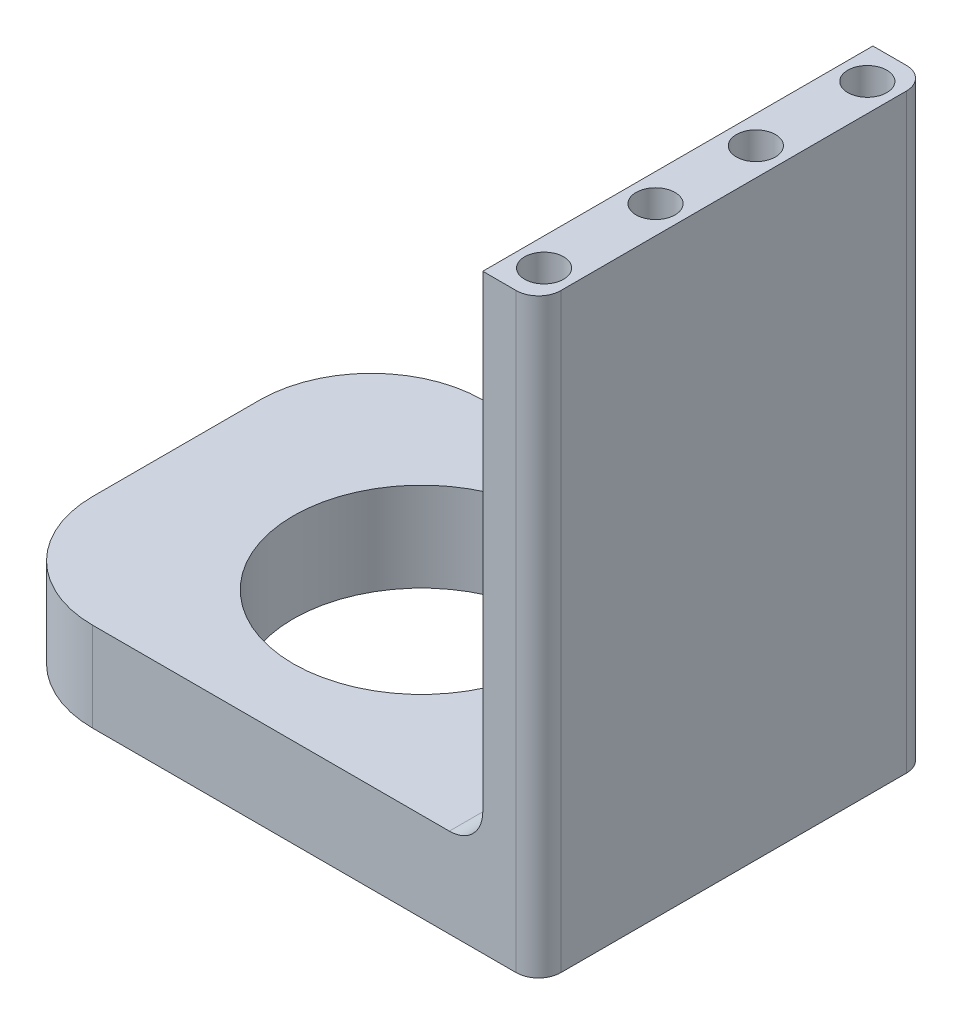
SolidWorks part; units mm, degrees
ref_plane "Front Plane" through (0, 0, 0) normal (0, 0, 1) x (1, 0, 0)
ref_plane "Top Plane" through (0, 0, 0) normal (0, 1, 0) x (1, 0, 0)
ref_plane "Right Plane" through (0, 0, 0) normal (1, 0, 0) x (0, 0, -1)
sketch "Sketch1" plane through (0, 0, 0) normal (0, 1, 0) x (1, 0, 0)
  line L1 (28, 17.5) -> (-22, 17.5)
  line L2 (28, 17.5) -> (28, -17.5)
  line L3 (28, -17.5) -> (-22, -17.5)
  line L4 (-22, 17.5) -> (-22, -17.5)
  circle A0 centre (0, 0) radius 11.5
  point P8 (28, 0)
  dimension "D1" = 23
  dimension "D2" = 35
  dimension "D3" = 50
  dimension "D4" = 28
extrude "Boss-Extrude1" add sketch "Sketch1" along normal blind 8
sketch "Sketch2" plane through (0, 8, 0) normal (0, 1, 0) x (1, 0, 0)
  line L0 (-22, -17.5) -> (28, -17.5) construction
  line L1 (28, 17.5) -> (23, 17.5)
  line L2 (28, 17.5) -> (28, -17.5)
  line L3 (28, -17.5) -> (23, -17.5)
  line L4 (23, 17.5) -> (23, -17.5)
  dimension "D1" = 5
extrude "Boss-Extrude2" add sketch "Sketch2" along normal blind 45
fillet "Fillet2" radius 3 1 edges at (23, 8, 0)
sketch "Sketch5" plane through (0, 53, 0) normal (0, 1, 0) x (1, 0, 0)
  line L0 (28, 17.5) -> (23, 17.5) construction
  line L1 (23, -17.5) -> (28, -17.5) construction
  circle A0 centre (25.5, 14.5) radius 1.75
  circle A1 centre (25.5, -14.5) radius 1.75
  circle A2 centre (25.5, 4.5) radius 1.75
  circle A3 centre (25.5, -4.5) radius 1.75
  point P3 (25.5, 17.5)
  dimension "D1" = 10
  dimension "D3" = 3.5
  dimension "D4" = 3
  dimension "D5" = 10
  dimension "D2" = 3
extrude "Cut-Extrude2" cut sketch "Sketch5" against normal blind 10
fillet "Fillet3" radius 10 2 edges at (-22, 4, 17.5) (-22, 4, -17.5)
fillet "Fillet4" radius 2 2 edges at (28, 26.5, 17.5) (28, 26.5, -17.5)
